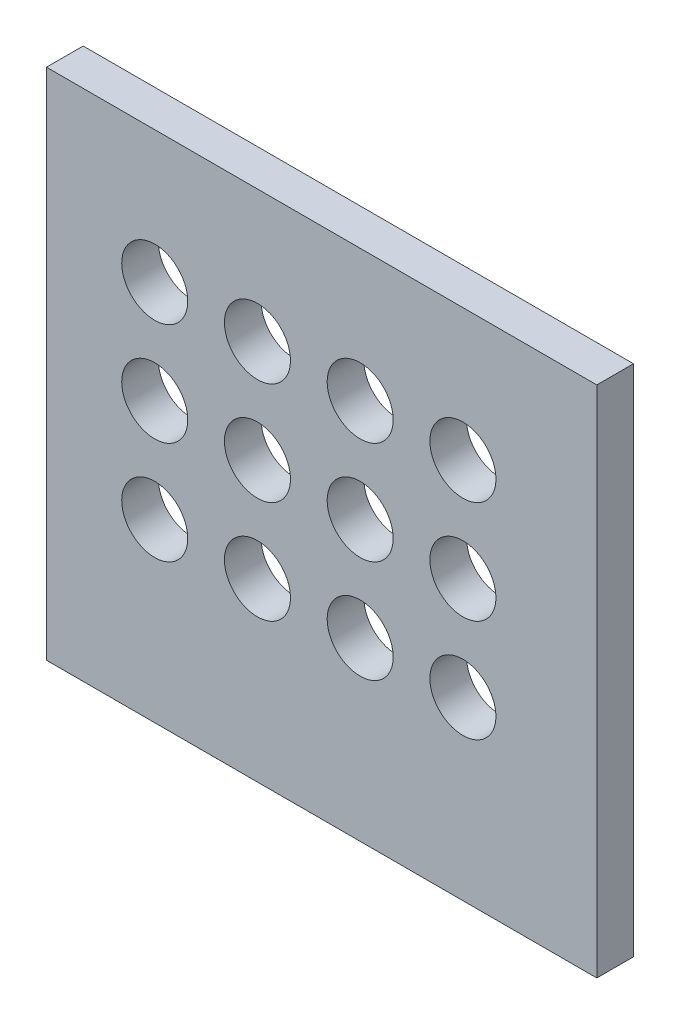
SolidWorks part; units mm, degrees
ref_plane "Front Plane" through (0, 0, 0) normal (0, 0, 1) x (1, 0, 0)
ref_plane "Top Plane" through (0, 0, 0) normal (0, 1, 0) x (1, 0, 0)
ref_plane "Right Plane" through (0, 0, 0) normal (1, 0, 0) x (0, 0, -1)
ref_plane "Plane4" through (0, 0, 10) normal (0, 0, 1) x (1, 0, 0)
sketch "Sketch1" plane through (0, 0, 10) normal (0, 0, 1) x (1, 0, 0)
  line L0 (-75, 70) -> (-75, -70)
  line L1 (-75, -70) -> (75, -70)
  line L2 (75, -70) -> (75, 70)
  line L3 (75, 70) -> (-75, 70)
  circle A0 centre (-17.5, -22) radius 9
  circle A1 centre (-45.5, -22) radius 9
  circle A2 centre (10.5, -22) radius 9
  circle A3 centre (38.5, -22) radius 9
  circle A4 centre (-45.5, 6) radius 9
  circle A5 centre (-17.5, 6) radius 9
  circle A6 centre (10.5, 6) radius 9
  circle A7 centre (38.5, 6) radius 9
  circle A8 centre (-45.5, 34) radius 9
  circle A9 centre (-17.5, 34) radius 9
  circle A10 centre (10.5, 34) radius 9
  circle A11 centre (38.5, 34) radius 9
  dimension "D1" = 18
  dimension "D2" = 10.5
  dimension "D3" = 38.5
  dimension "D4" = 75
  dimension "D5" = 17.5
  dimension "D6" = 45.5
  dimension "D7" = 75
  dimension "D8" = 6
  dimension "D9" = 34
  dimension "D10" = 70
  dimension "D11" = 22
  dimension "D12" = 70
extrude "Boss-Extrude1" add sketch "Sketch1" against normal blind 10
